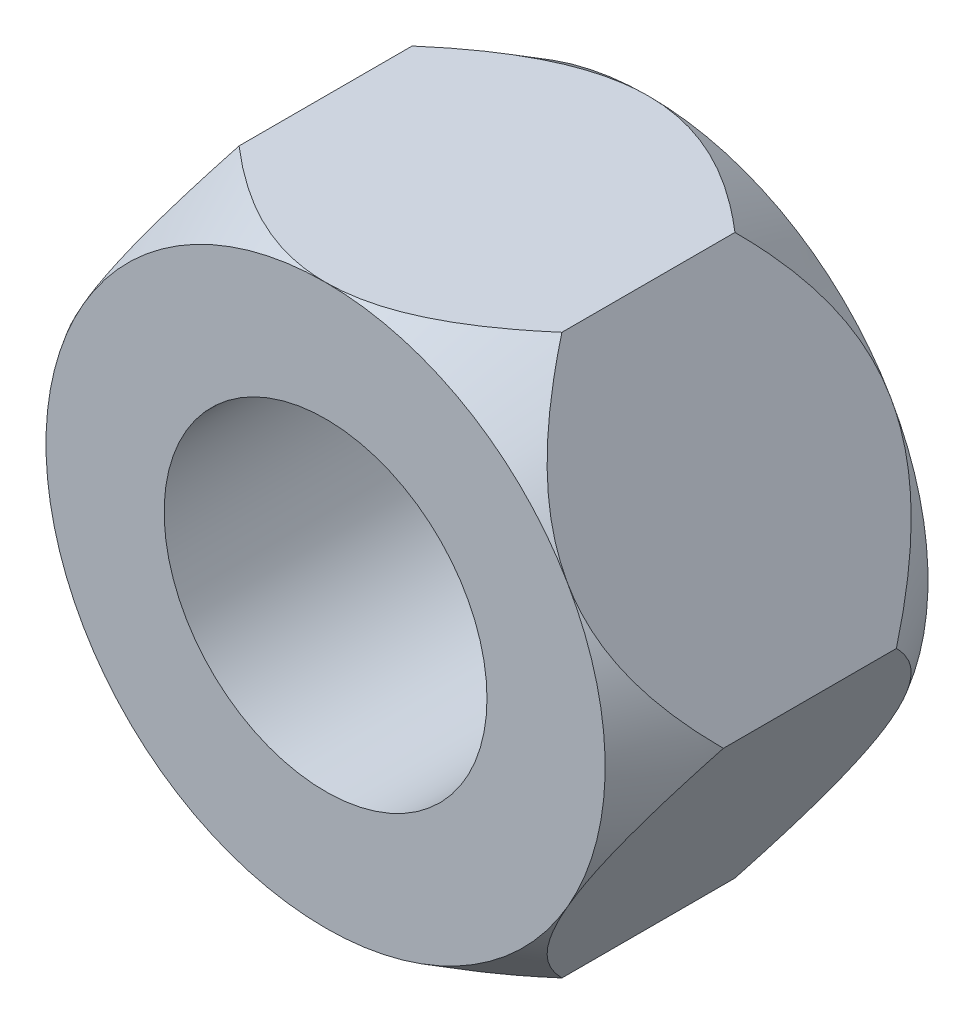
SolidWorks part; units mm, degrees
ref_plane "Front Plane" through (0, 0, 0) normal (0, 0, 1) x (1, 0, 0)
ref_plane "Top Plane" through (0, 0, 0) normal (0, 1, 0) x (1, 0, 0)
ref_plane "Right Plane" through (0, 0, 0) normal (1, 0, 0) x (0, 0, -1)
sketch "Sketch1" plane through (0, 0, 0) normal (0, 0, 1) x (1, 0, 0)
  line L1 (8, 0) -> (4, 6.9282)
  line L2 (4, 6.9282) -> (-4, 6.9282)
  line L3 (-4, 6.9282) -> (-8, 0)
  line L4 (-8, 0) -> (-4, -6.9282)
  line L5 (-4, -6.9282) -> (4, -6.9282)
  line L6 (4, -6.9282) -> (8, 0)
  circle A0 centre (0, 0) radius 6.9282 construction
  dimension "D1" = 16
extrude "Boss-Extrude1" add sketch "Sketch1" along normal mid plane 8
sketch "Sketch2" plane through (0, 0, 4) normal (0, 0, 1) x (1, 0, 0)
  line L0 (8, 0) -> (4, 6.9282) construction
  circle A0 centre (0, 0) radius 6.9282
extrude "Cut-Extrude1" cut sketch "Sketch2" against normal blind 8 draft 30 flip side to cut
mirror "Mirror1" about plane through (0, 0, 0) normal (0, 0, 1) of "Cut-Extrude1"
sketch "Sketch3" plane through (0, 0, 4) normal (0, 0, 1) x (1, 0, 0)
  circle A0 centre (0, 0) radius 4
  dimension "D1" = 8
extrude "Cut-Extrude2" cut sketch "Sketch3" against normal blind 8
